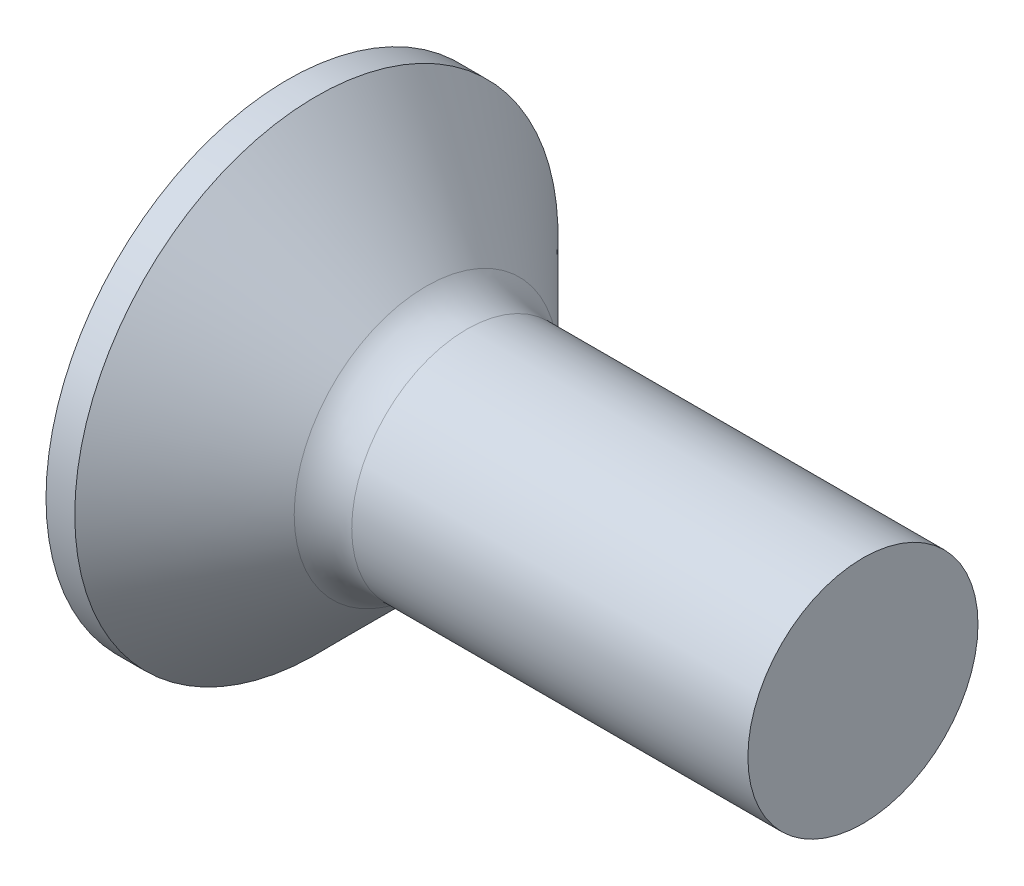
SolidWorks part; units mm, degrees
revolve "Base-Revolve" add sketch "BodySke"
sketch "BodySke" plane through (0, 0, 0) normal (0, 0, 1) x (1, 0, 0)
  line L0 (0, 0) -> (0, 4.2)
  line L1 (0, 4.2) -> (0.5, 4.2)
  line L2 (2.7, 2) -> (10, 2)
  line L3 (10, 2) -> (10, 0)
  line L4 (10, 0) -> (0, 0)
  line L5 (-6.35, 0) -> (82.55, 0) construction
  line L6 (2.7, -2) -> (10, -2) construction
  line L7 (0.5, -4.2) -> (2.7, -2) construction
  line L8 (0.5, 4.2) -> (2.7, 2)
  line L9 (0, -4.2) -> (0.5, -4.2) construction
  line L10 (3.4, 3.5875) -> (3.4, -5.9375) construction
  line L11 (0, 6.35) -> (0, -3.175) construction
  dimension "Diameter" = 4
  dimension "Length" = 10
  dimension "Head_ht" = 2.7
  dimension "Head_dia" = 8.4
  dimension "Head_ang" = 90
  dimension "D6" = 0.5
  dimension "Advance" = 0.7
  dimension "Thread_nom" = 10
cosmetic thread "ThreadCosmetic" [suppressed]
fillet "Fillet1" radius 1 1 edges at (2.7, 0, 2)
ref_plane "Plane1" through (0, 0, 0) normal (0, 0, 1) x (1, 0, 0)
ref_plane "Plane2" through (0, 0, 0) normal (0, 1, 0) x (1, 0, 0)
ref_plane "Plane3" through (0, 0, 0) normal (1, 0, 0) x (0, 0, -1)
other "Configuration Table"
sketch "Sketch3" plane through (0, 0, 0) normal (-1, 0, 0) x (0, 0, 1)
  line L0 (-0.515, 2.2) -> (0.515, 2.2)
  line L1 (0.515, 2.2) -> (0.515, -2.2)
  line L2 (0.515, -2.2) -> (-0.515, -2.2)
  line L3 (-0.515, -2.2) -> (-0.515, 2.2)
  dimension "Cross_dia" = 4.4
  dimension "Cross_width" = 1.03
  dimension "D1" = 2.2
  dimension "D2" = 0.515
ref_plane "Plane4" through (2.51, 0, 0) normal (-1, 0, 0) x (0, 0, 1)
sketch "Sketch4" plane through (2.51, 0, 0) normal (-1, 0, 0) x (0, 0, 1)
  line L0 (-0.515, 0.9486) -> (0.515, 0.9486)
  line L3 (0.515, 0.9486) -> (0.515, -0.9486)
  line L4 (0.515, -0.9486) -> (-0.515, -0.9486)
  line L5 (-0.515, -0.9486) -> (-0.515, 0.9486)
  dimension "D2" = 1.8971
  dimension "D1" = 1.03
  dimension "D4" = 0.9486
  dimension "D3" = 0.515
loft "Recess" cut profiles "Sketch3", "Sketch4"
pattern_circular "RecPat" count 2 every 90 about axis through (0, 0, 0) along (1, 0, 0) of "Recess"
sketch "RecCorSke" plane through (0, 0, 0) normal (0, 0, 1) x (1, 0, 0)
  line L0 (-3.175, 0) -> (15.875, 0) construction
  line L2 (0, 0) -> (0, 1.0265)
  line L3 (0, 1.0265) -> (2.51, 0.851)
  line L4 (2.51, 0.851) -> (2.7865, 0)
  line L5 (2.7865, 0) -> (0, 0)
  dimension "Diameter" = 1.702
  dimension "Depth" = 2.51
  dimension "Draft_angle" = 4
  dimension "Bottom_angle" = 18
revolve "RecessCore" cut sketch "RecCorSke" angle 360 about L0
sketch "ThdSchSke" plane through (0, 0, 0) normal (0, 0, 1) x (1, 0, 0)
  line L0 (3.4, -1.61) -> (3.1269, -2)
  line L1 (3.4, -1.61) -> (3.6731, -2)
  line L2 (3.6731, -2) -> (3.6731, -2.5)
  line L3 (-3.175, 0) -> (5.1513, 0) construction
  line L5 (3.6731, -2.5) -> (3.1269, -2.5)
  line L6 (3.1269, -2.5) -> (3.1269, -2)
  line L7 (0, 4.2) -> (0, -4.2) construction
  dimension "Diameter" = 4
  dimension "Thread_minor" = 3.22
  dimension "Start" = 3.4
revolve "ThreadSchematic" [suppressed] cut sketch "ThdSchSke" angle 360 about L3
pattern_linear "ThdSchPat" [suppressed]
equation "\"D1@Sketch3\" = \"Cross_dia@Sketch3\" / 2"
equation "\"D2@Sketch3\" = \"Cross_width@Sketch3\" / 2"
equation "\"Depth@RecCorSke\" = \"Cross_depth@Plane4\""
equation "\"D1@Sketch4\" = \"Cross_width@Sketch3\""
equation "\"D2@Sketch4\" = \"Cross_dia@Sketch3\" - 2.0 * \"Cross_depth@Plane4\" * tan(26.5  * 0.017453292)"
equation "\"D3@Sketch4\" = \"D1@Sketch4\" / 2"
equation "\"D4@Sketch4\" = \"D2@Sketch4\" / 2"
equation "\"Thread_length@ThreadCosmetic\" = ((sgn( (\"Length@BodySke\" - \"Advance@BodySke\" * 1.0 - \"Head_ht@BodySke\" ) - \"Thread_nom@BodySke\" )-1)*( (\"Length@BodySke\" - \"Advance@BodySke\" * 1.0 - \"Head_ht@BodySke\" ) - \"Thread_nom@BodySke\" ))/-2+ \"Thread_nom@BodySke\""
equation "\"Thread_minor@ThdSchSke\" = \"Thread_minor@ThreadCosmetic\""
equation "\"Diameter@ThdSchSke\" = \"Diameter@BodySke\""
equation "\"Overcut@ThdSchSke\" = \"Diameter@BodySke\" * 1.25"
equation "\"Start@ThdSchSke\" = 0.000001 + \"Length@BodySke\" - \"Thread_length@ThreadCosmetic\"  '---Countersunk---"
equation "\"Num_threads@ThdSchPat\" = int( \"Thread_length@ThreadCosmetic\" / \"Advance@BodySke\" + 0.999 )  + 1"
equation "\"Advance@ThdSchPat\" = \"Thread_length@ThreadCosmetic\" /  (\"Num_threads@ThdSchPat\" - 1) 'relax it"
